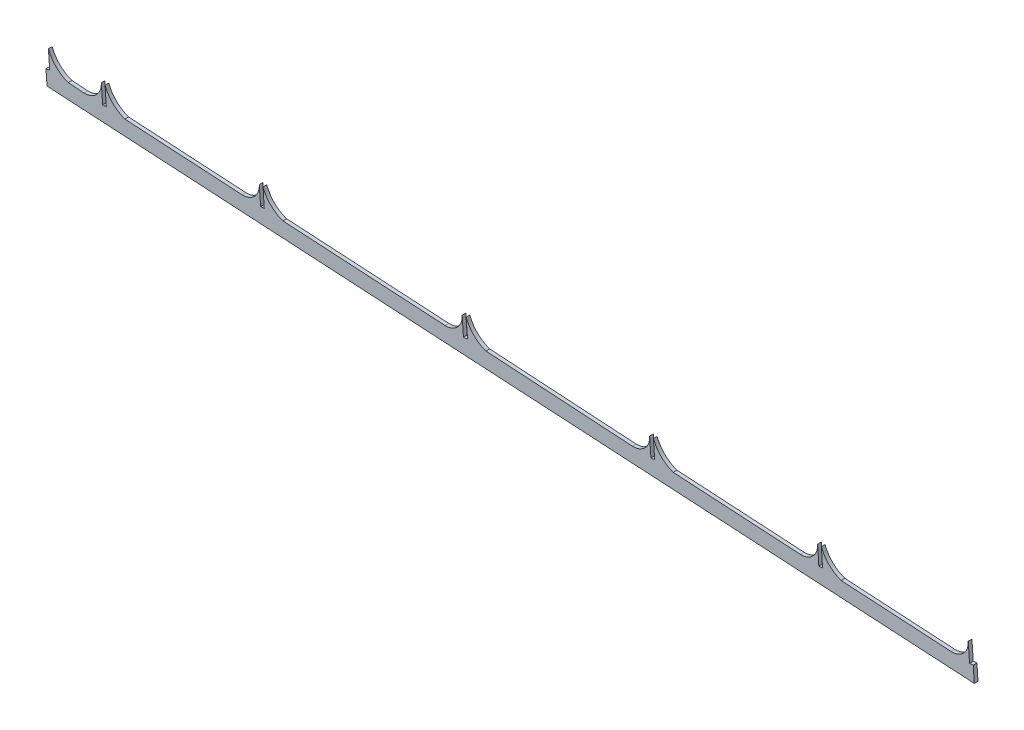
SolidWorks part; units mm, degrees
ref_plane "前视基准面" through (0, 0, 0) normal (0, 0, 1) x (1, 0, 0)
ref_plane "上视基准面" through (0, 0, 0) normal (0, 1, 0) x (1, 0, 0)
ref_plane "右视基准面" through (0, 0, 0) normal (1, 0, 0) x (0, 0, -1)
sketch "Model" plane through (0, 0, 0) normal (0, 0, 1) x (1, 0, 0)
  line L0 (1009.8452, 241.6691) -> (509.6069, 270.6241)
  line L2 (916.0144, 255.0485) -> (847.4114, 259.0912)
  line L3 (825.4279, 260.2918) -> (746.3882, 265.2411)
  line L4 (724.2732, 266.1469) -> (636.8121, 271.2812)
  line L5 (614.8286, 272.4818) -> (551.5961, 276.2137)
  line L6 (529.6126, 277.4143) -> (521.0491, 277.9818)
  line L7 (1007.275, 249.754) -> (1009.2701, 249.8935)
  line L8 (925.9954, 254.5034) -> (927.9905, 254.6429)
  line L9 (835.4064, 259.7834) -> (837.4015, 259.9229)
  line L10 (734.2532, 265.6155) -> (736.4977, 265.7724)
  line L11 (624.8104, 271.9255) -> (626.8055, 272.0651)
  line L12 (539.5958, 276.8387) -> (541.5909, 276.9782)
  line L13 (511.0509, 278.6444) -> (509.0558, 278.5049)
  line L14 (510.3643, 288.4637) -> (511.0509, 278.6444)
  line L15 (509.0558, 278.5049) -> (509.6069, 270.6241)
  line L16 (538.8984, 286.8121) -> (539.5958, 276.8387)
  line L17 (540.9114, 286.6956) -> (541.5909, 276.9782)
  line L18 (624.1143, 281.8796) -> (624.8104, 271.9255)
  line L19 (626.1274, 281.7631) -> (626.8055, 272.0651)
  line L20 (733.5589, 275.5447) -> (734.2532, 265.6155)
  line L21 (735.7034, 275.723) -> (736.4977, 265.7724)
  line L22 (834.7137, 269.6896) -> (835.4064, 259.7834)
  line L23 (836.7267, 269.5731) -> (837.4015, 259.9229)
  line L24 (925.3001, 264.4463) -> (925.9954, 254.5034)
  line L25 (927.3131, 264.3297) -> (927.9905, 254.6429)
  line L26 (1006.5766, 259.7418) -> (1007.275, 249.754)
  line L27 (1009.2701, 249.8935) -> (1009.8452, 241.6691)
  line L28 (937.9979, 253.8479) -> (997.2909, 250.344)
  arc A0 (997.2909, 250.344) -> (1006.5766, 259.7418) centre (997.7165, 259.2098) ccw
  arc A1 (927.3131, 264.3297) -> (937.9979, 253.8479) centre (943.9666, 270.6189) ccw
  arc A2 (916.0144, 255.0485) -> (925.3001, 264.4463) centre (916.44, 263.9143) ccw
  arc A3 (825.4279, 260.2918) -> (834.7137, 269.6896) centre (825.8536, 269.1576) ccw
  arc A4 (724.2732, 266.1469) -> (733.5589, 275.5447) centre (724.6989, 275.0127) ccw
  arc A5 (614.8286, 272.4818) -> (624.1143, 281.8796) centre (615.2543, 281.3476) ccw
  arc A6 (529.6126, 277.4143) -> (538.8984, 286.8121) centre (530.0383, 286.2801) ccw
  arc A7 (836.7267, 269.5731) -> (847.4114, 259.0912) centre (853.3802, 275.8622) ccw
  arc A8 (735.7034, 275.723) -> (746.3882, 265.2411) centre (752.3569, 282.0121) ccw
  arc A9 (626.1274, 281.7631) -> (636.8121, 271.2812) centre (642.7809, 288.0522) ccw
  arc A10 (540.9114, 286.6956) -> (551.5961, 276.2137) centre (557.5649, 292.9847) ccw
  arc A11 (510.3643, 288.4637) -> (521.0491, 277.9818) centre (527.0178, 294.7528) ccw
extrude "凸台-拉伸3" add sketch "Model" along normal blind 2
